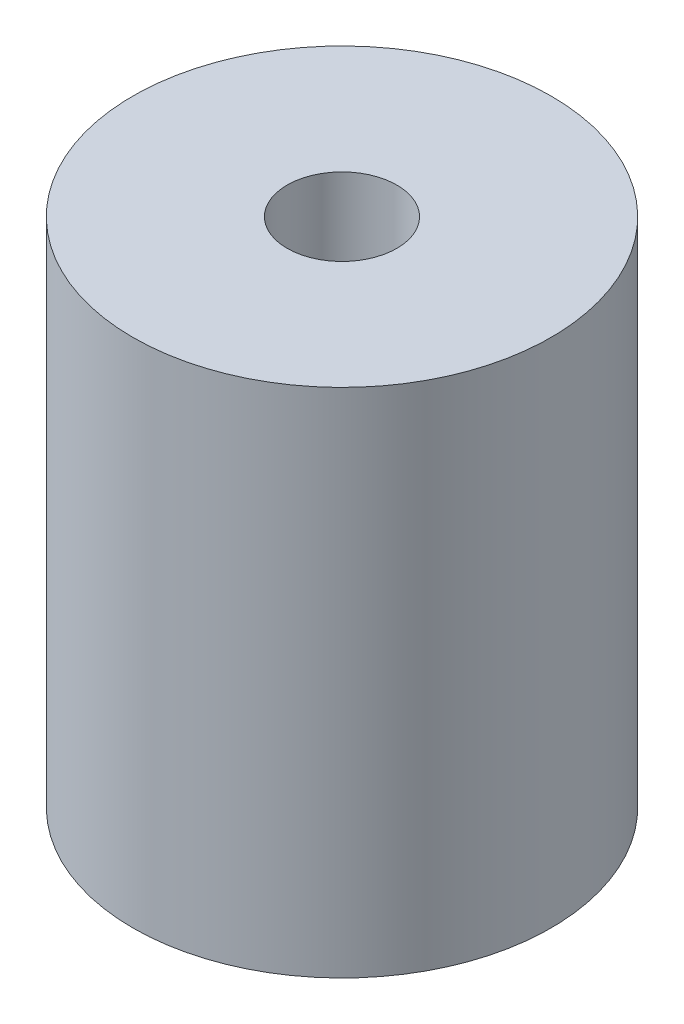
SolidWorks part; units mm, degrees
ref_plane "Front Plane" through (0, 0, 0) normal (0, 0, 1) x (1, 0, 0)
ref_plane "Top Plane" through (0, 0, 0) normal (0, 1, 0) x (1, 0, 0)
ref_plane "Right Plane" through (0, 0, 0) normal (1, 0, 0) x (0, 0, -1)
sketch "Sketch1" plane through (0, 0, 0) normal (0, 1, 0) x (1, 0, 0)
  circle A0 centre (0, 0) radius 9.525
  dimension "D1" = 19.05
extrude "Boss-Extrude1" add sketch "Sketch1" along normal blind 23.3
hole_wizard "Ø5.0mm Dowel Hole1" positions "Sketch2" profile "Sketch3" hole size "Ø5.0" standard "ANSI Metric" end condition through all
sketch "Sketch2" plane through (0, 23.3, 0) normal (0, 1, 0) x (1, 0, 0)
  point P0 (0, 0)
sketch "Sketch3" plane through (0, 23.3, 0) normal (1, 0, 0) x (0, 0, 1)
  line L0 (0, 0) -> (0, 23.3)
  line L1 (0, 23.3) -> (2.5, 23.3)
  line L2 (2.5, 23.3) -> (2.5, 0)
  line L5 (2.5, 0) -> (0, 0)
  line L11 (0, -6.35) -> (0, 107.95) construction
  dimension "Thru Hole Dia." = 5
  dimension "Thru Hole Depth" = 23.3
